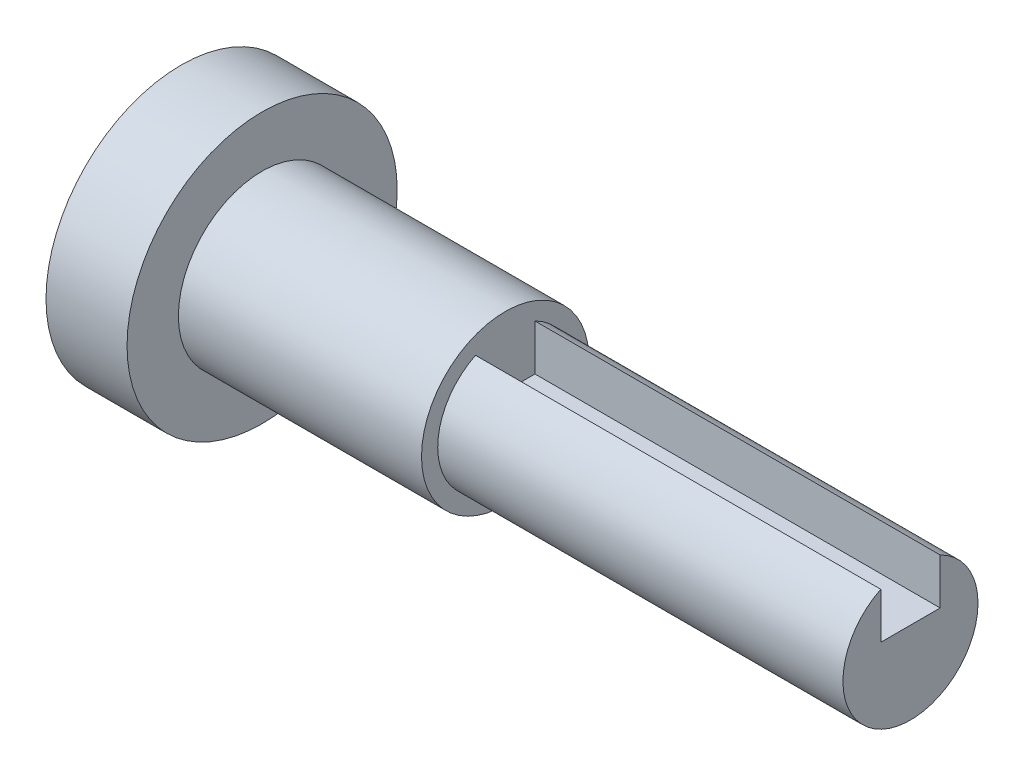
SolidWorks part; units mm, degrees
ref_plane "Front Plane" through (0, 0, 0) normal (0, 0, 1) x (1, 0, 0)
ref_plane "Top Plane" through (0, 0, 0) normal (0, 1, 0) x (1, 0, 0)
ref_plane "Right Plane" through (0, 0, 0) normal (1, 0, 0) x (0, 0, -1)
sketch "Sketch1" plane through (0, 0, 0) normal (0, 0, 1) x (1, 0, 0)
  line L0 (0, 0) -> (27, 0)
  line L1 (27, 0) -> (27, 2.5)
  line L2 (27, 2.5) -> (12, 2.5)
  line L3 (12, 2.5) -> (12, 3.1)
  line L4 (12, 3.1) -> (3, 3.1)
  line L5 (3, 3.1) -> (3, 5)
  line L6 (3, 5) -> (0, 5)
  line L7 (0, 5) -> (0, 0)
  dimension "D1" = 5
  dimension "D2" = 3.1
  dimension "D3" = 2.5
  dimension "D4" = 15
  dimension "D5" = 3
  dimension "D6" = 9
revolve "Revolve1" add sketch "Sketch1" angle 360 about L0
sketch "Sketch2" plane through (27, 0, 0) normal (1, 0, 0) x (0, 0, -1)
  line L0 (0, 0) -> (0, 3.8927) construction
  line L1 (-1.1, 2.245) -> (-1.1, 0.545)
  line L2 (-1.1, 0.545) -> (1.1, 0.545)
  line L3 (1.1, 0.545) -> (1.1, 2.245)
  line L4 (-1.1, 2.245) -> (0, 3.0598)
  line L5 (0, 3.0598) -> (1.1, 2.245)
  circle A0 centre (0, 0) radius 2.5 construction
  dimension "D1" = 2.2
  dimension "D2" = 1.7
extrude "Cut-Extrude1" cut sketch "Sketch2" against normal up to surface (15 mm away) up to face at (12, 0, 3.1)
